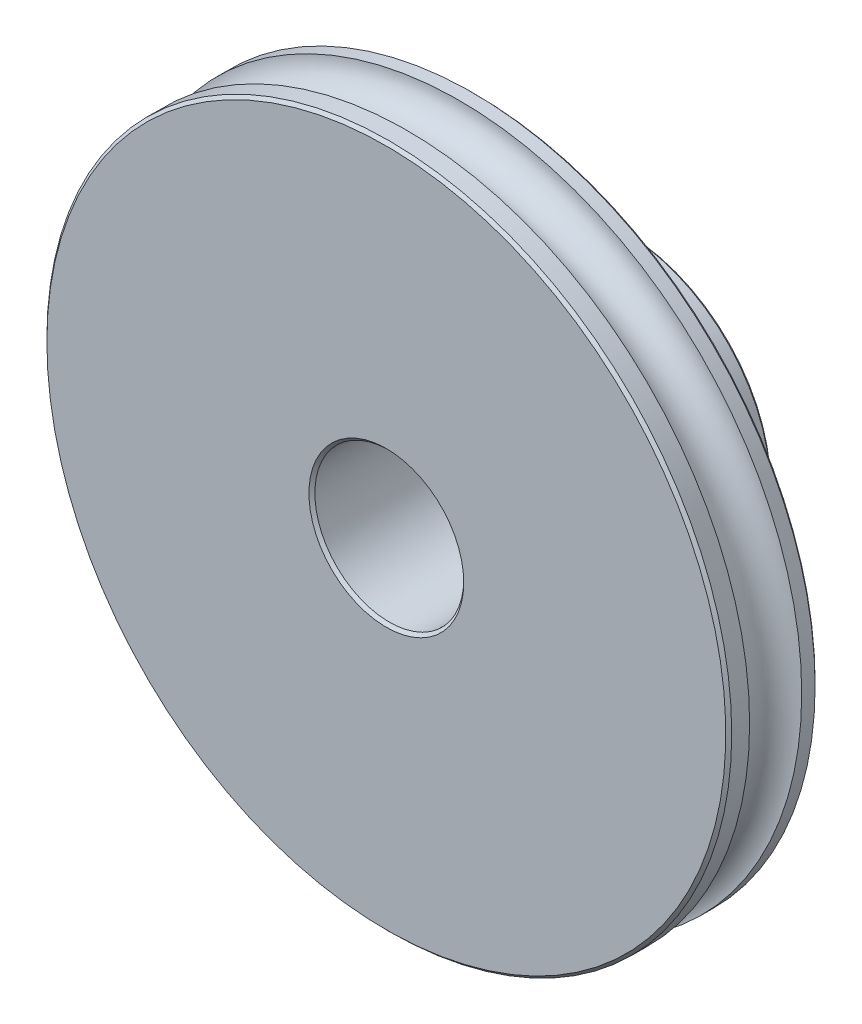
SolidWorks part; units mm, degrees
ref_plane "前视基准面" through (0, 0, 0) normal (0, 0, 1) x (1, 0, 0)
ref_plane "上视基准面" through (0, 0, 0) normal (0, 1, 0) x (1, 0, 0)
ref_plane "右视基准面" through (0, 0, 0) normal (1, 0, 0) x (0, 0, -1)
sketch "草图1" plane through (0, 0, 0) normal (1, 0, 0) x (0, 0, -1)
  line L0 (0, 0) -> (46.9269, 0) construction
  line L1 (0.8616, 5) -> (16.8616, 5)
  line L2 (0.8616, 23) -> (2.2616, 23)
  line L3 (5.7616, 23) -> (6.8616, 23)
  line L6 (16.8616, 10) -> (6.8616, 10)
  line L7 (6.8616, 23) -> (6.8616, 10)
  line L9 (16.8616, 10) -> (16.8616, 5)
  line L10 (0.8616, 23) -> (0.8616, 5)
  arc A0 (2.2616, 23) -> (5.7616, 23) centre (4.0116, 23) ccw
  dimension "D2" = 3.5
  dimension "D1" = 5
  dimension "D3" = 23
  dimension "D6" = 10
  dimension "D8" = 10
  dimension "D9" = 16
revolve "旋转1" add sketch "草图1" angle 360 about L0
hole_wizard "M4 螺纹孔1" positions "草图3" profile "草图2" tap size "M4" standard "GB"
sketch "草图3" plane through (0, 0, 0) normal (0, 1, 0) x (1, 0, 0)
  point P0 (0, 12)
sketch "草图2" plane through (0, 0, -12) normal (1, 0, 0) x (0, 0, -1)
  line L0 (0, 0) -> (0, 31.4186)
  line L1 (0, 31.4186) -> (2, 31.4186)
  line L2 (2, 31.4186) -> (2, 0)
  line L5 (2, 0) -> (0, 0)
  line L11 (0, -6.35) -> (0, 107.95) construction
  dimension "螺纹线主直径" = 4
  dimension "通孔螺纹孔钻头深度" = 31.4186
pattern_circular "阵列(圆周)1" count 2 every 120 about axis through (0, 0, 0) along (0, 0, 1) of "M4 螺纹孔1"
chamfer "倒角1" distance 0.2 angle 45 5 edges at (5, 0, -0.8616) (5, 0, -16.8616) (10, 0, -16.8616) (23, 0, -0.8616) (23, 0, -6.8616)
chamfer "倒角2" distance 0.5 angle 45 1 edges at (10, 0, -6.8616)
